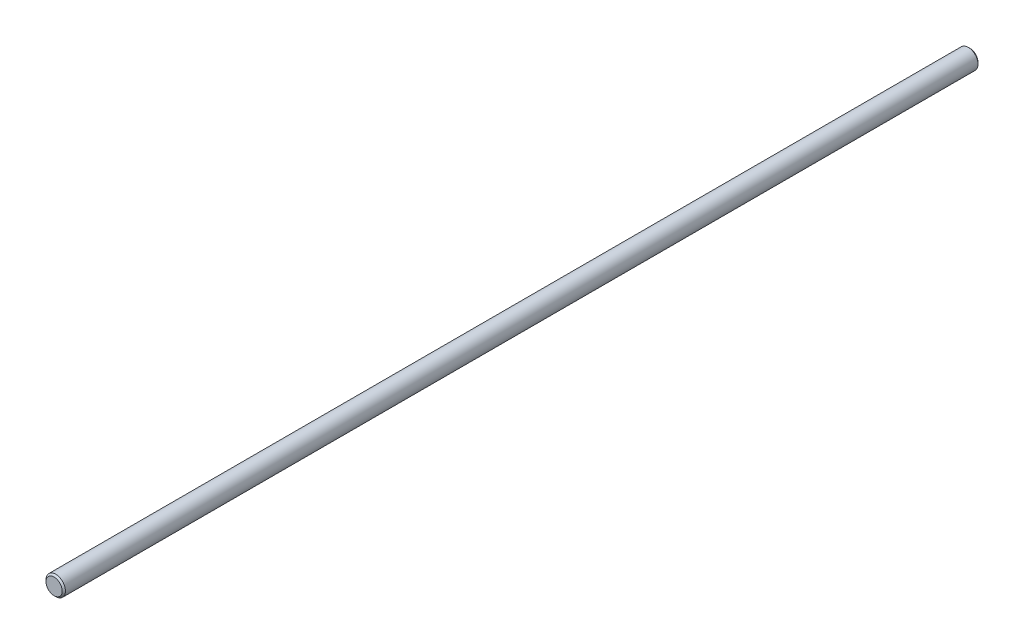
SolidWorks part; units mm, degrees
material "AISI 1020 Steel, Cold Rolled"
ref_plane "Front Plane" through (0, 0, 0) normal (0, 0, 1) x (1, 0, 0)
ref_plane "Top Plane" through (0, 0, 0) normal (0, 1, 0) x (1, 0, 0)
ref_plane "Right Plane" through (0, 0, 0) normal (1, 0, 0) x (0, 0, -1)
sketch "Sketch1" plane through (0, 0, 0) normal (0, 0, 1) x (1, 0, 0)
  circle A0 centre (0, 0) radius 3
  dimension "D1" = 6
extrude "Boss-Extrude1" add sketch "Sketch1" along normal mid plane 282.5
chamfer "Chamfer1" distance 0.5 angle 45 2 edges at (3, 0, -141.25) (3, 0, 141.25)
